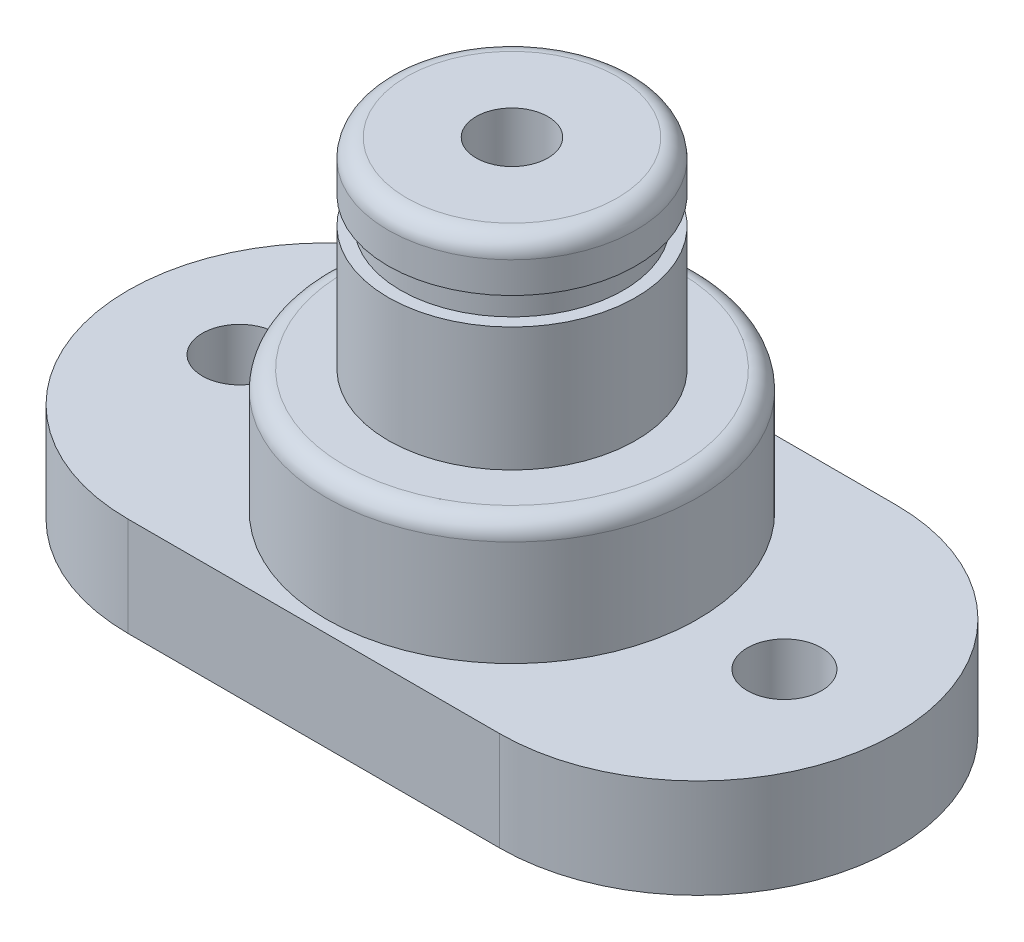
SolidWorks part; units mm, degrees
material "6061 合金"
ref_plane "前视基准面" through (0, 0, 0) normal (0, 0, 1) x (1, 0, 0)
ref_plane "上视基准面" through (0, 0, 0) normal (0, 1, 0) x (1, 0, 0)
ref_plane "右视基准面" through (0, 0, 0) normal (1, 0, 0) x (0, 0, -1)
sketch "草图8" plane through (0, 0, 0) normal (0, 1, 0) x (1, 0, 0)
  line L0 (0, -13.1096) -> (0, 16.071) construction
  line L1 (7.5, 8) -> (-7.5, 8)
  line L2 (7.5, 8) -> (7.5, -8)
  line L3 (7.5, -8) -> (-7.5, -8)
  line L4 (-7.5, 8) -> (-7.5, -8)
  line L5 (7.5, 8) -> (-7.5, -8) construction
  line L6 (7.5, -8) -> (-7.5, 8) construction
  line L7 (-15.5, 0) -> (15, 0) construction
  arc A0 (-7.5, 8) -> (-7.5, -8) centre (-7.5, 0) ccw
  circle A2 centre (-11, 0) radius 1.5
  circle A3 centre (11, 0) radius 1.5
  arc A4 (7.5, -8) -> (7.5, 8) centre (7.5, 0) ccw
  point P0 (0, 0)
  dimension "D1" = 15
  dimension "D3" = 22
  dimension "D4" = 3
  dimension "D2" = 16
extrude "凸台-拉伸4" add sketch "草图8" along normal blind 4 contours L4 A0 A2 | L1 L4 L3 L2 | L2 A4 A3
sketch "草图9" plane through (0, 4, 0) normal (0, 1, 0) x (1, 0, 0)
  circle A0 centre (0, 0) radius 7.5
  dimension "D1" = 15
extrude "凸台-拉伸5" add sketch "草图9" along normal blind 5 contours A0
sketch "草图10" plane through (0, 9, 0) normal (0, 1, 0) x (1, 0, 0)
  circle A0 centre (0, 0) radius 5
  dimension "D1" = 10
extrude "凸台-拉伸6" add sketch "草图10" along normal blind 5
sketch "草图12" plane through (0, 14, 0) normal (0, 1, 0) x (1, 0, 0)
  circle A0 centre (0, 0) radius 4.5
  dimension "D1" = 9
extrude "凸台-拉伸7" add sketch "草图12" along normal blind 1.1
sketch "草图14" plane through (0, 0, 0) normal (0, -1, 0) x (1, 0, 0)
  circle A0 centre (0, 0) radius 1.45
  dimension "D1" = 2.9
extrude "切除-拉伸1" cut sketch "草图14" against normal through all
sketch "草图15" plane through (0, 15.1, 0) normal (0, 1, 0) x (1, 0, 0)
  circle A0 centre (0, 0) radius 5
  dimension "D1" = 10
extrude "凸台-拉伸8" add sketch "草图15" along normal blind 2
fillet "圆角2" radius 0.75 2 edges at (0, 9, 7.5) (0, 17.1, 5)
sketch "草图16" plane through (0, 0, 0) normal (0, -1, 0) x (-1, 0, 0)
  circle A0 centre (0, 0) radius 1.45
  dimension "D1" = 2.9
extrude "切除-拉伸2" cut sketch "草图16" against normal through all
